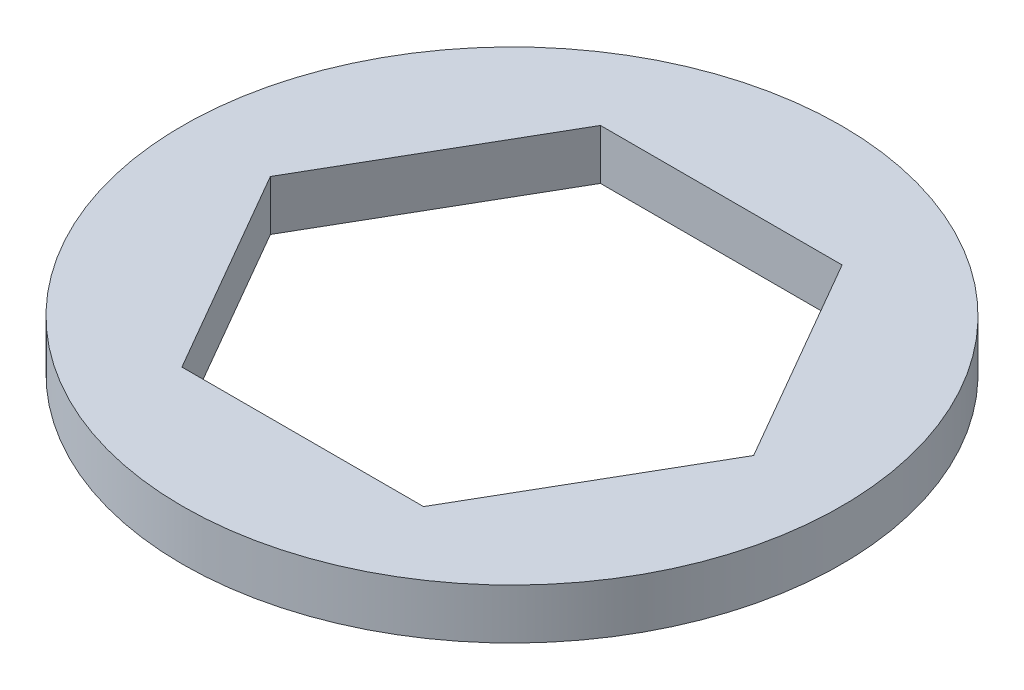
SolidWorks part; units mm, degrees
ref_plane "Front Plane" through (0, 0, 0) normal (0, 0, 1) x (1, 0, 0)
ref_plane "Top Plane" through (0, 0, 0) normal (0, 1, 0) x (1, 0, 0)
ref_plane "Right Plane" through (0, 0, 0) normal (1, 0, 0) x (0, 0, -1)
sketch "Sketch1" plane through (0, 0, 0) normal (0, 1, 0) x (1, 0, 0)
  line L1 (-7.3323, 0) -> (-3.6662, -6.35)
  line L2 (-3.6662, -6.35) -> (3.6662, -6.35)
  line L3 (3.6662, -6.35) -> (7.3323, 0)
  line L4 (7.3323, 0) -> (3.6662, 6.35)
  line L5 (3.6662, 6.35) -> (-3.6662, 6.35)
  line L6 (-3.6662, 6.35) -> (-7.3323, 0)
  circle A0 centre (0, 0) radius 10
  circle A1 centre (0, 0) radius 6.35 construction
  dimension "D2" = 20
  dimension "D1" = 12.7
extrude "Boss-Extrude1" add sketch "Sketch1" along normal blind 1.524
